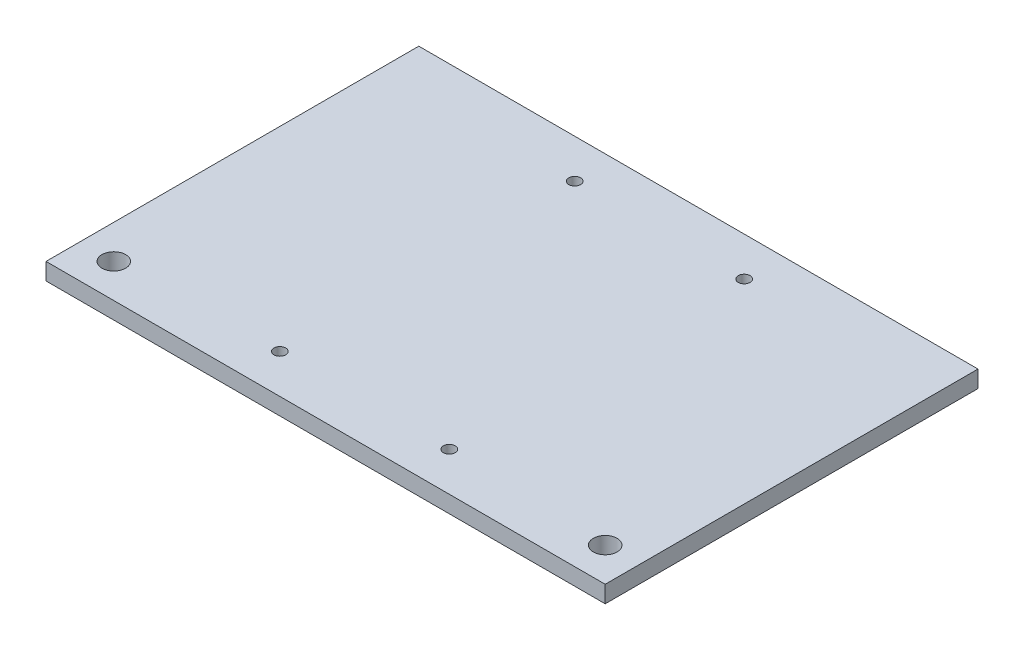
SolidWorks part; units mm, degrees
ref_plane "Front Plane" through (0, 0, 0) normal (0, 0, 1) x (1, 0, 0)
ref_plane "Top Plane" through (0, 0, 0) normal (0, 1, 0) x (1, 0, 0)
ref_plane "Right Plane" through (0, 0, 0) normal (1, 0, 0) x (0, 0, -1)
sketch "Sketch1" plane through (0, 0, 0) normal (0, 1, 0) x (1, 0, 0)
  line L0 (82.5, 55) -> (-82.5, 55)
  line L2 (-82.5, 55) -> (-82.5, -55)
  line L3 (-82.5, -55) -> (82.5, -55)
  line L4 (82.5, 55) -> (82.5, -55)
  line L5 (-82.5, 55) -> (82.5, -55) construction
  line L6 (-82.5, -55) -> (82.5, 55) construction
  line L7 (25, -43.5) -> (-25, -43.5) construction
  line L8 (25, -43.5) -> (25, 43.5) construction
  line L9 (25, 43.5) -> (-25, 43.5) construction
  line L10 (-25, -43.5) -> (-25, 43.5) construction
  line L11 (25, -43.5) -> (-25, 43.5) construction
  line L12 (25, 43.5) -> (-25, -43.5) construction
  circle A0 centre (72.5, -45) radius 3.5
  circle A1 centre (-72.5, -45) radius 3.5
  circle A2 centre (25, -43.5) radius 1.75
  circle A3 centre (-25, -43.5) radius 1.75
  circle A12 centre (-25, 43.5) radius 1.75
  circle A13 centre (25, 43.5) radius 1.75
  point P0 (0, 0)
  point P10 (0, 0)
  point P16 (0, 0)
  point P17 (0, 0)
  point P18 (0, 0)
  dimension "D3" = 7
  dimension "D10" = 3.5
  dimension "D1" = 110
  dimension "D2" = 165
  dimension "D4" = 10
  dimension "D5" = 10
  dimension "D6" = 10
  dimension "D7" = 87
  dimension "D8" = 50
  dimension "D11" = 25
extrude "Boss-Extrude1" add sketch "Sketch1" along normal blind 5
